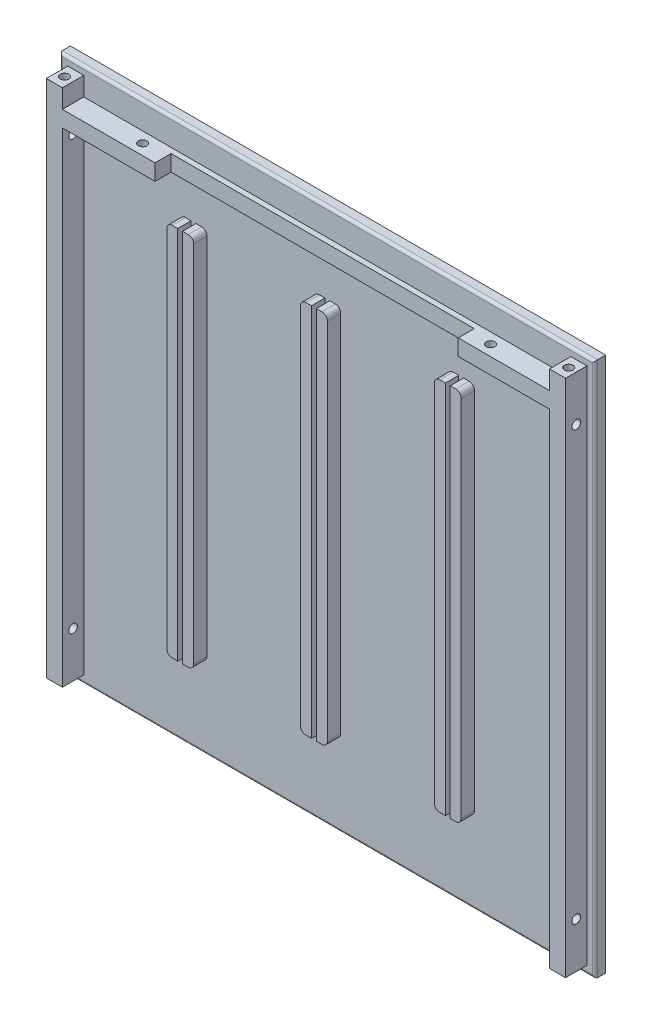
SolidWorks part; units mm, degrees
ref_plane "Plan de face" through (0, 0, 0) normal (0, 0, 1) x (1, 0, 0)
ref_plane "Plan de dessus" through (0, 0, 0) normal (0, 1, 0) x (1, 0, 0)
ref_plane "Plan de droite" through (0, 0, 0) normal (1, 0, 0) x (0, 0, -1)
sketch "Esquisse1" plane through (0, 0, 0) normal (0, 0, 1) x (1, 0, 0)
  line L1 (0, 0) -> (200, 0)
  line L2 (0, 0) -> (0, 200)
  line L3 (0, 200) -> (200, 200)
  line L4 (200, 0) -> (200, 200)
  dimension "D1" = 200
  dimension "D2" = 200
extrude "Boss.-Extru. Paroie" add sketch "Esquisse1" along normal blind 4
sketch "Esquisse2" plane through (0, 0, 4) normal (0, 0, 1) x (1, 0, 0)
  line L0 (0, 0) -> (200, 0) construction
  line L1 (47, 170) -> (53, 170)
  line L2 (45, 168) -> (45, 32)
  line L3 (47, 30) -> (53, 30)
  line L4 (55, 168) -> (55, 32)
  line L5 (0, 200) -> (0, 0) construction
  line L18 (97, 170) -> (103, 170)
  line L19 (95, 168) -> (95, 32)
  line L20 (97, 30) -> (103, 30)
  line L21 (105, 168) -> (105, 32)
  line L22 (147, 170) -> (153, 170)
  line L23 (145, 168) -> (145, 32)
  line L24 (147, 30) -> (153, 30)
  line L25 (155, 168) -> (155, 32)
  arc A0 (45, 32) -> (47, 30) centre (47, 32) ccw
  arc A1 (53, 30) -> (55, 32) centre (53, 32) ccw
  arc A2 (53, 170) -> (55, 168) centre (53, 168) cw
  arc A3 (47, 170) -> (45, 168) centre (47, 168) ccw
  arc A16 (95, 32) -> (97, 30) centre (97, 32) ccw
  arc A17 (103, 30) -> (105, 32) centre (103, 32) ccw
  arc A18 (103, 170) -> (105, 168) centre (103, 168) cw
  arc A19 (97, 170) -> (95, 168) centre (97, 168) ccw
  arc A20 (145, 32) -> (147, 30) centre (147, 32) ccw
  arc A21 (153, 30) -> (155, 32) centre (153, 32) ccw
  arc A22 (153, 170) -> (155, 168) centre (153, 168) cw
  arc A23 (147, 170) -> (145, 168) centre (147, 168) ccw
  point P10 (45, 30)
  point P15 (55, 170)
  point P18 (45, 170)
  dimension "D5" = 2
  dimension "D1" = 10
  dimension "D2" = 140
  dimension "D3" = 30
  dimension "D4" = 45
  dimension "D6" = 3
sketch "Esquisse4" plane through (0, 0, 4) normal (0, 0, 1) x (1, 0, 0)
  line L0 (3, 3) -> (9, 3)
  line L6 (0, 0) -> (200, 0) construction
  line L17 (9, 3) -> (9, 184)
  line L18 (9, 184) -> (191, 184)
  line L19 (191, 184) -> (191, 3)
  line L20 (191, 3) -> (197, 3)
  line L21 (197, 3) -> (197, 197)
  line L22 (197, 197) -> (191, 197)
  line L24 (191, 197) -> (191, 190)
  line L26 (191, 190) -> (9, 190)
  line L27 (9, 190) -> (9, 197)
  line L28 (9, 197) -> (3, 197)
  line L29 (3, 197) -> (3, 3)
  line L31 (0, 200) -> (0, 0) construction
  line L32 (200, 200) -> (0, 200) construction
  line L33 (200, 0) -> (200, 200) construction
  dimension "D1" = 6
  dimension "D2" = 3
  dimension "D3" = 3
  dimension "D4" = 6
  dimension "D5" = 6
  dimension "D6" = 3
  dimension "D7" = 3
  dimension "D8" = 6
  dimension "D9" = 3
  dimension "D10" = 10
  dimension "D11" = 3
  dimension "D12" = 6
extrude "Boss.-Extru. Bords" add sketch "Esquisse4" along normal blind 8
extrude "Boss.-Extru. Glissieres" add sketch "Esquisse2" along normal blind 5
fillet "Congé1" radius 1 4 edges at (200, 100, 4) (100, 200, 4) (0, 100, 4) (100, 0, 4)
sketch "Esquisse8" plane through (0, 0, 4) normal (0, 0, 1) x (1, 0, 0)
  line L0 (0, 200) -> (0, 0) construction
  line L1 (99.1, 175) -> (100.9, 175)
  line L2 (99.1, 175) -> (99.1, -5)
  line L3 (99.1, -5) -> (100.9, -5)
  line L4 (100.9, 175) -> (100.9, -5)
  line L5 (200, 200) -> (0, 200) construction
  line L6 (149.1, 175) -> (150.9, 175)
  line L7 (149.1, 175) -> (149.1, -5)
  line L8 (149.1, -5) -> (150.9, -5)
  line L9 (150.9, 175) -> (150.9, -5)
  line L10 (49.1, 175) -> (50.9, 175)
  line L11 (49.1, 175) -> (49.1, -5)
  line L12 (49.1, -5) -> (50.9, -5)
  line L13 (50.9, 175) -> (50.9, -5)
  dimension "D1" = 1.8
  dimension "D2" = 99.1
  dimension "D3" = 180
  dimension "D4" = 25
  dimension "D5" = 2
  dimension "D6" = 2
extrude "Enlèv. mat.-Extru.6" cut sketch "Esquisse8" along normal through all
sketch "Esquisse5" plane through (3, 0, 0) normal (-1, 0, 0) x (0, 0, 1)
  line L0 (12, 3) -> (4, 3) construction
  line L1 (12, 197) -> (4, 197) construction
  circle A0 centre (8, 180) radius 1.6
  circle A1 centre (8, 20) radius 1.6
  dimension "D1" = 17
  dimension "D2" = 17
extrude "Enlèv. mat.-Extru.2" cut sketch "Esquisse5" against normal blind 10
sketch "Esquisse6" plane through (197, 0, 0) normal (1, 0, 0) x (0, 0, -1)
  line L0 (0, 0) -> (0, 200) construction
  line L1 (-12, 197) -> (-4, 197) construction
  line L2 (-12, 3) -> (-4, 3) construction
  circle A0 centre (-8, 180) radius 1.6
  circle A1 centre (-8, 20) radius 1.6
  dimension "D1" = 8
  dimension "D2" = 3.2
  dimension "D3" = 17
  dimension "D4" = 17
extrude "Enlèv. mat.-Extru.3" cut sketch "Esquisse6" against normal blind 10
sketch "Esquisse7" plane through (0, 184, 0) normal (0, -1, 0) x (1, 0, 0)
  line L0 (9, 12) -> (191, 12) construction
  line L1 (9, 12) -> (9, 4) construction
  line L2 (50, 4) -> (50, 17.1304) construction
  line L3 (9, 4) -> (191, 4) construction
  circle A0 centre (35, 8) radius 1.6
  circle A1 centre (165, 8) radius 1.6
  dimension "D1" = 4
  dimension "D4" = 15
  dimension "D5" = 26
  dimension "D2" = 4
  dimension "D3" = 130
extrude "Enlèv. mat.-Extru.4" cut sketch "Esquisse7" against normal blind 10
sketch "Esquisse9" plane through (0, 197, 0) normal (0, 1, 0) x (1, 0, 0)
  line L0 (200, -3) -> (200, 0) construction
  line L2 (0, -3) -> (0, 0) construction
  line L4 (200, 0) -> (0, 0) construction
  circle A0 centre (194.2, -8) radius 1.6
  circle A1 centre (5.8, -8) radius 1.6
  dimension "D1" = 5.8
  dimension "D3" = 5.8
  dimension "D2" = 8
  dimension "D4" = 8
sketch "Esquisse10" plane through (0, 3, 0) normal (0, -1, 0) x (-1, 0, 0)
  circle A0 centre (-194.2, -8) radius 1.6
  circle A1 centre (-5.8, -8) radius 1.6
extrude "Enlèv. mat.-Extru.8" cut sketch "Esquisse10" against normal blind 10
sketch "Esquisse11" plane through (0, 0, 12) normal (0, 0, 1) x (1, 0, 0)
  line L0 (191, 190) -> (9, 190) construction
  line L1 (156.9004, 190) -> (43.5972, 190)
  line L2 (156.9004, 190) -> (156.9004, 184)
  line L3 (156.9004, 184) -> (43.5972, 184)
  line L4 (43.5972, 190) -> (43.5972, 184)
  line L5 (9, 184) -> (191, 184) construction
extrude "Enlèv. mat.-Extru.9" cut sketch "Esquisse11" against normal blind 6
extrude "Enlèv. mat.-Extru.10" cut sketch "Esquisse9" against normal blind 10
